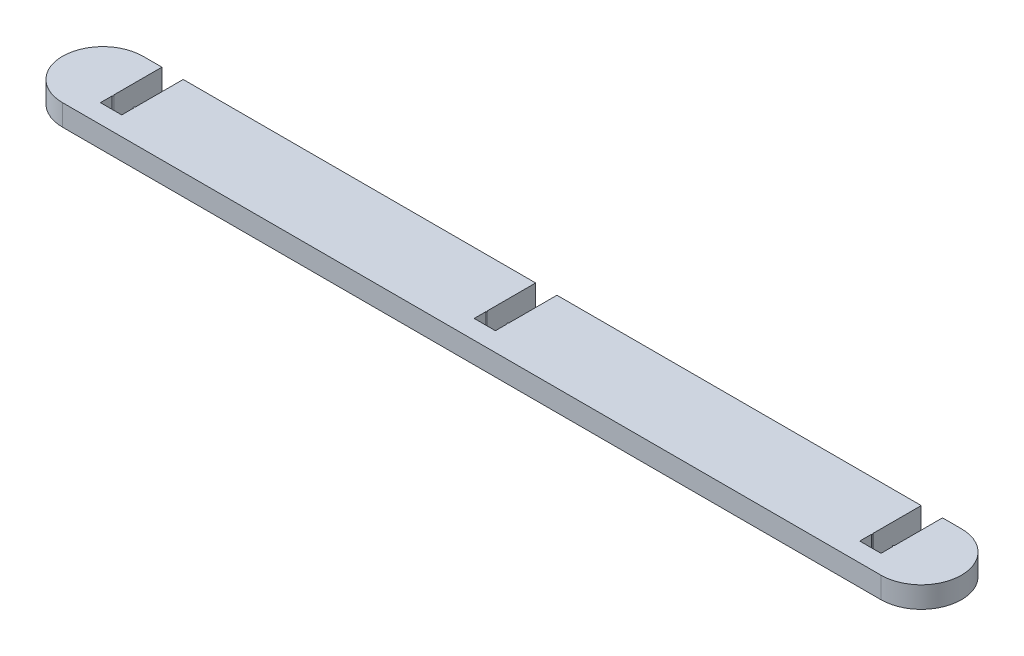
SolidWorks part; units mm, degrees
ref_plane "Front Plane" through (0, 0, 0) normal (0, 0, 1) x (1, 0, 0)
ref_plane "Top Plane" through (0, 0, 0) normal (0, 1, 0) x (1, 0, 0)
ref_plane "Right Plane" through (0, 0, 0) normal (1, 0, 0) x (0, 0, -1)
sketch "Sketch1" plane through (0, 0, 0) normal (0, 1, 0) x (1, 0, 0)
  line L0 (40.9212, 2.4526) -> (83.4212, 2.4526)
  line L1 (-46.5788, 2.4526) -> (-42.5788, 2.4526)
  line L2 (-46.5788, 2.4526) -> (-46.5788, -14.5474) construction
  line L3 (-46.5788, -14.5474) -> (126.4212, -14.5474)
  line L4 (126.4212, 2.4526) -> (126.4212, -14.5474) construction
  line L5 (87.9212, 2.4526) -> (117.9212, 2.4526)
  line L6 (-42.5788, 2.4526) -> (-42.5788, -7.7494)
  line L7 (-42.5788, -10.5474) -> (-38.0788, -10.5474)
  line L8 (-38.0788, 2.4526) -> (-38.0788, -7.7494)
  line L9 (-38.0788, 2.4526) -> (-8.0788, 2.4526)
  line L10 (-8.0788, 2.4526) -> (-8.0788, -10.5474) construction
  line L11 (-8.0788, -10.5474) -> (-3.5788, -10.5474) construction
  line L12 (-3.5788, 2.4526) -> (-3.5788, -10.5474) construction
  line L13 (83.4212, 2.4526) -> (83.4212, -10.5474) construction
  line L14 (36.4212, 2.4526) -> (36.4212, -7.7477)
  line L15 (36.4212, -10.5474) -> (40.9212, -10.5474)
  line L16 (40.9212, 2.4526) -> (40.9212, -7.7477)
  line L17 (83.4212, -10.5474) -> (87.9212, -10.5474) construction
  line L18 (87.9212, 2.4526) -> (87.9212, -10.5474) construction
  line L19 (87.9212, 2.4526) -> (83.4212, 2.4526)
  line L20 (117.9212, 2.4526) -> (117.9212, -7.7514)
  line L21 (117.9212, -10.5474) -> (122.4212, -10.5474)
  line L22 (122.4212, 2.4526) -> (122.4212, -7.7425)
  line L23 (122.4212, 2.4526) -> (126.4212, 2.4526)
  line L24 (-3.5788, 2.4526) -> (-8.0788, 2.4526)
  line L25 (-42.5788, -7.7494) -> (-42.5788, -8.0474) construction
  line L26 (-3.5788, 2.4526) -> (36.4212, 2.4526)
  line L27 (-42.5788, -8.0474) -> (-42.5788, -10.5474)
  line L28 (-38.0788, -7.7494) -> (-38.0788, -8.0474) construction
  line L29 (-38.0788, -8.0474) -> (-38.0788, -10.5474)
  line L30 (36.4212, -7.7477) -> (36.4212, -8.0474) construction
  line L31 (36.4212, -8.0474) -> (36.4212, -10.5474)
  line L32 (40.9212, -7.7477) -> (40.9212, -8.0474) construction
  line L33 (40.9212, -8.0474) -> (40.9212, -10.5474)
  line L34 (117.9212, -7.7514) -> (117.9212, -8.0474) construction
  line L35 (117.9212, -8.0474) -> (117.9212, -10.5474)
  line L36 (122.4212, -8.0474) -> (122.4212, -10.5474)
  line L37 (122.4212, -7.7425) -> (122.4212, -8.0474) construction
  line L38 (-38.5519, -10.5474) -> (-38.5519, -14.5474) construction
  line L39 (39.8936, -10.5474) -> (39.9212, -14.5474) construction
  line L40 (120.651, -10.5474) -> (120.651, -14.5474) construction
  arc A0 (-46.5788, 2.4526) -> (-46.5788, -14.5474) centre (-46.5788, -6.0474) ccw
  arc A1 (126.4212, 2.4526) -> (126.4212, -14.5474) centre (126.4212, -6.0474) cw
  arc A2 (-42.5788, -8.0474) -> (-42.5788, -7.7494) centre (-42.5788, -7.8984) ccw
  arc A3 (-38.0788, -7.7494) -> (-38.0788, -8.0474) centre (-38.0788, -7.8984) ccw
  arc A4 (36.4212, -8.0474) -> (36.4212, -7.7477) centre (36.4212, -7.8975) ccw
  arc A5 (40.9212, -7.7477) -> (40.9212, -8.0474) centre (40.9212, -7.8975) ccw
  arc A6 (117.9212, -7.7514) -> (117.9212, -8.0474) centre (117.9212, -7.8994) cw
  arc A7 (122.4212, -7.7425) -> (122.4212, -8.0474) centre (122.4212, -7.8949) ccw
  dimension "D10" = 2.5
  dimension "D11" = 0.149
  dimension "D12" = 0.149
  dimension "D13" = 0.1499
  dimension "D14" = 0.1499
  dimension "D17" = 0.148
  dimension "D18" = 0.1525
  dimension "D1" = 17
  dimension "D2" = 4.5
  dimension "D3" = 4
  dimension "D4" = 30
  dimension "D5" = 40
  dimension "D6" = 42.5
  dimension "D7" = 30
  dimension "D8" = 4
  dimension "D9" = 4
  dimension "D15" = 2.5
  dimension "D16" = 2.5
  dimension "D19" = 2.5
  dimension "D20" = 4
extrude "Boss-Extrude1" add sketch "Sketch1" along normal blind 4.5
ref_plane "Plane1" through (-38.0788, 55.3224, -2.4526) normal (0, 0, 1) x (1, 0, 0)
